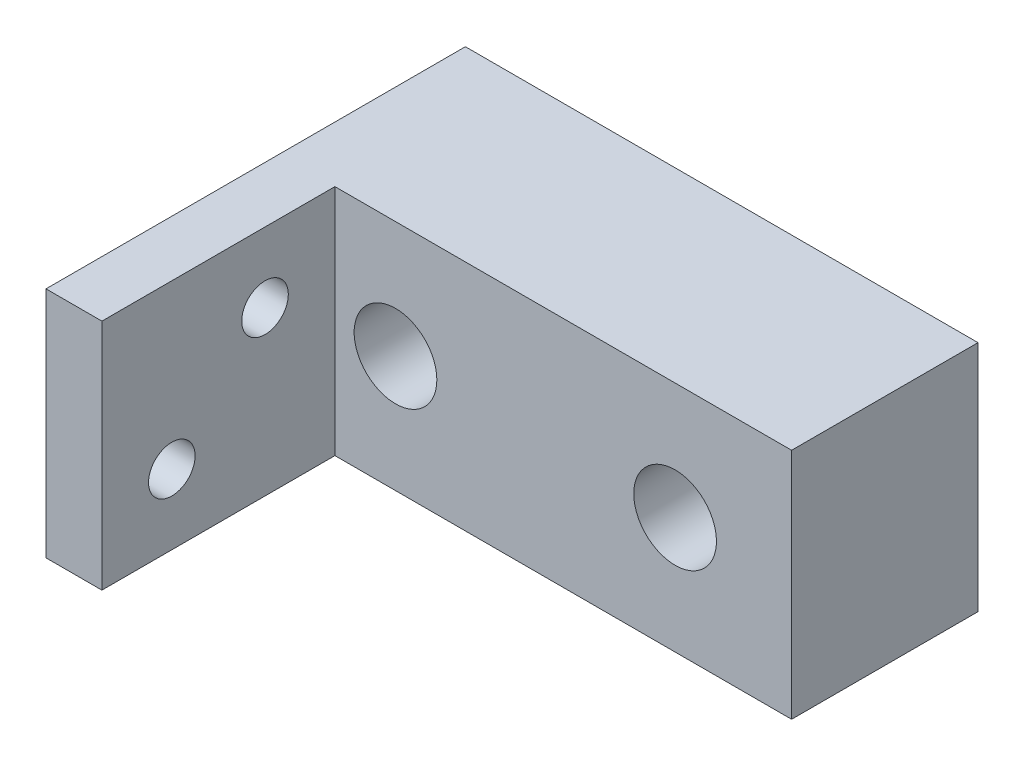
SolidWorks part; units mm, degrees
ref_plane "前视基准面" through (0, 0, 0) normal (0, 0, 1) x (1, 0, 0)
ref_plane "上视基准面" through (0, 0, 0) normal (0, 1, 0) x (1, 0, 0)
ref_plane "右视基准面" through (0, 0, 0) normal (1, 0, 0) x (0, 0, -1)
sketch "草图1" plane through (0, 0, 0) normal (0, 0, 1) x (1, 0, 0)
  line L0 (-50.1813, 20.3278) -> (4.8187, 20.3278)
  line L1 (4.8187, 20.3278) -> (4.8187, -4.6722)
  line L2 (4.8187, -4.6722) -> (-50.1813, -4.6722)
  line L3 (-50.1813, -4.6722) -> (-50.1813, 20.3278)
  line L4 (-22.6813, -4.6722) -> (-22.6813, 37.5063) construction
  circle A0 centre (-37.6813, 7.8278) radius 4.4359
  circle A1 centre (-7.6813, 7.8278) radius 4.4359
  dimension "D1" = 55
  dimension "D2" = 25
  dimension "D3" = 12.5
  dimension "D4" = 12.5
extrude "凸台-拉伸1" add sketch "草图1" along normal blind 20
sketch "草图2" plane through (0, 0, 20) normal (0, 0, 1) x (1, 0, 0)
  line L0 (-50.1813, 20.3278) -> (-44.1813, 20.3278)
  line L1 (4.8187, 20.3278) -> (-50.1813, 20.3278) construction
  line L2 (-44.1813, 20.3278) -> (-44.1813, -4.6722)
  line L3 (-50.1813, -4.6722) -> (4.8187, -4.6722) construction
  line L4 (-44.1813, -4.6722) -> (-50.1813, -4.6722)
  line L5 (-50.1813, -4.6722) -> (-50.1813, 20.3278)
  dimension "D1" = 6
extrude "凸台-拉伸2" add sketch "草图2" along normal blind 25
sketch "草图3" plane through (-44.1813, 0, 0) normal (1, 0, 0) x (0, 0, -1)
  line L0 (-45, -4.6722) -> (-20, -4.6722) construction
  line L1 (-45, -4.6722) -> (-45, 20.3278) construction
  circle A0 centre (-37.5, 2.8278) radius 2.5
  circle A1 centre (-27.5, 12.8278) radius 2.5
  dimension "D1" = 5
  dimension "D2" = 5
  dimension "D3" = 10
  dimension "D4" = 7.5
  dimension "D5" = 10
  dimension "D6" = 7.5
extrude "切除-拉伸1" cut sketch "草图3" against normal through all contours A0 | A1
